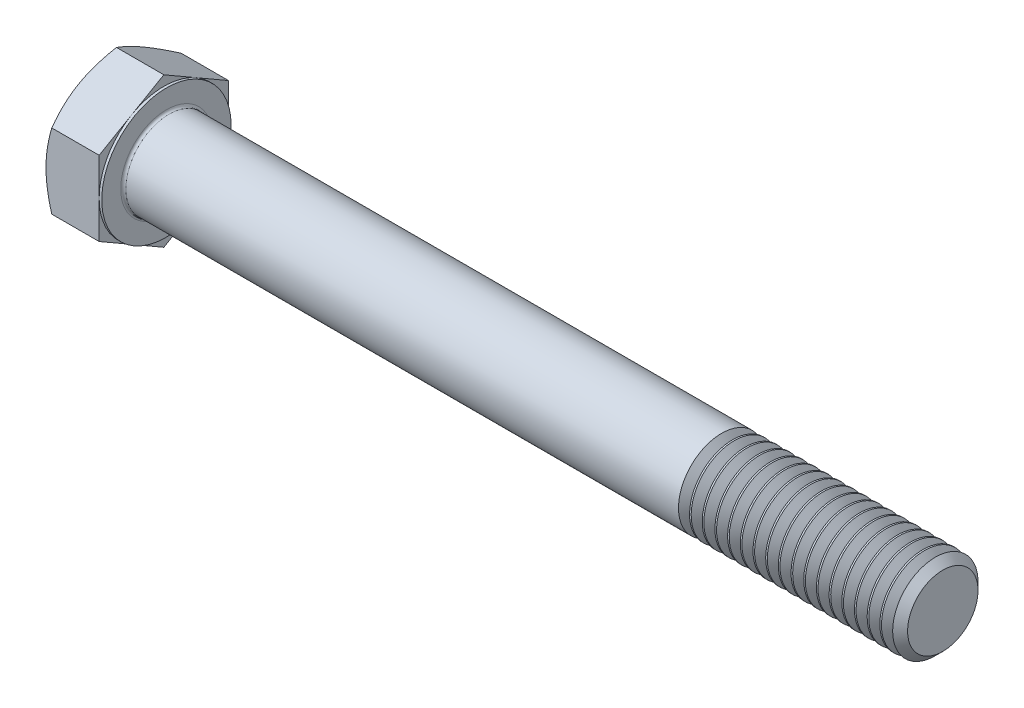
SolidWorks part; units mm, degrees
extrude "BaseHead" add sketch "Sketch1" along normal blind 8.2042
sketch "Sketch1" plane through (0, 0, 0) normal (1, 0, 0) x (0, 0, -1)
  line L0 (9.525, 5.4993) -> (9.525, -5.4993)
  line L1 (-9.525, 5.4993) -> (-9.525, -5.4993)
  line L2 (9.525, -5.4993) -> (0, -10.9985)
  line L3 (0, -10.9985) -> (-9.525, -5.4993)
  line L4 (9.525, 5.4993) -> (0, 10.9985)
  line L5 (0, 10.9985) -> (-9.525, 5.4993)
  dimension "Width_flats" = 19.05
  dimension "D2" = 120
  dimension "D3" = 9.525
  dimension "D4" = 9.525
  dimension "D5" = 9.525
revolve "HeadChamfer" cut sketch "Sketch3" angle 360 about L6
sketch "Sketch3" plane through (0, 0, 0) normal (0, 0, 1) x (1, 0, 0)
  line L0 (0, 9.525) -> (4.5169, 17.3485)
  line L1 (0, 10.9985) -> (0, 5.4993) construction
  line L2 (4.5169, 17.3485) -> (4.5169, 23.6985)
  line L3 (4.5169, 23.6985) -> (-12.7, 23.6985)
  line L4 (-12.7, 23.6985) -> (-12.7, 9.525)
  line L5 (-12.7, 9.525) -> (0, 9.525)
  line L6 (0, 0) -> (99.06, 0) construction
  line L7 (8.2042, 10.9985) -> (0, 10.9985) construction
  dimension "D1" = 9.525
  dimension "D2" = 6.35
  dimension "D3" = 12.7
  dimension "D4" = 6.35
  dimension "Head_ch_ang" = 30
material "Plain Carbon Steel"
ref_plane "Plane1" through (0, 0, 0) normal (0, 0, 1) x (1, 0, 0)
ref_plane "Plane2" through (0, 0, 0) normal (0, 1, 0) x (1, 0, 0)
ref_plane "Plane3" through (0, 0, 0) normal (1, 0, 0) x (0, 0, -1)
sketch "BodySke" plane through (0, 0, 0) normal (0, 0, 1) x (1, 0, 0)
  line L0 (0, 5.4993) -> (0, -5.4993) construction
  line L1 (0, 0) -> (122.5042, 0)
  line L2 (0, 0) -> (0, 6.35)
  line L3 (0, 6.35) -> (121.3409, 6.35)
  line L4 (122.5042, 0) -> (122.5042, 5.1867)
  line L5 (8.2042, 10.9985) -> (8.2042, 5.4993) construction
  line L6 (122.5042, 5.1867) -> (121.3409, 6.35)
  line L7 (0, 0) -> (96.52, 0) construction
  line L8 (122.5042, -5.1867) -> (121.3409, -6.35) construction
  line L9 (0, -6.35) -> (121.3409, -6.35) construction
  line L10 (10.1575, 15.24) -> (10.1575, -1.27) construction
  line L11 (90.7542, 15.24) -> (90.7542, -1.27) construction
  line L12 (8.2042, 5.4993) -> (8.2042, -5.4993) construction
  dimension "Diameter" = 12.7
revolve "BaseBody" add sketch "BodySke" angle 360 about L7
cosmetic thread "ThreadCosmetic" [suppressed]
sketch "Sketch4" plane through (0, 0, 0) normal (0, 0, 1) x (1, 0, 0)
  line L1 (8.2042, 10.9985) -> (8.2042, 5.4993) construction
  line L2 (8.2042, 9.525) -> (7.8232, 9.525)
  line L3 (8.2042, 9.525) -> (8.2042, 36.3985)
  line L4 (8.2042, 36.3985) -> (7.8232, 36.3985)
  line L5 (0, 0) -> (95.25, 0) construction
  line L6 (0, 0) -> (96.52, 0) construction
  line L7 (7.8232, 9.525) -> (7.8232, 36.3985)
  line L8 (8.2042, 10.9985) -> (0.8507, 10.9985) construction
  dimension "D1" = 9.525
  dimension "D2" = 25.4
revolve "BearingFace" cut sketch "Sketch4" angle 360 about L5
fillet "HeadFillet" radius 0.381 1 edges at (8.2042, 0, -6.35)
sketch "ThdSchSke" plane through (0, 0, 0) normal (0, 0, 1) x (1, 0, 0)
  line L0 (90.7542, -5.1867) -> (89.9396, -6.35)
  line L1 (90.7542, -5.1867) -> (91.5688, -6.35)
  line L2 (91.5688, -6.35) -> (91.5688, -7.9375)
  line L3 (-3.175, 0) -> (5.1513, 0) construction
  line L5 (91.5688, -7.9375) -> (89.9396, -7.9375)
  line L6 (89.9396, -7.9375) -> (89.9396, -6.35)
  dimension "Thread_minor" = 10.3734
  dimension "Diameter" = 12.7
  dimension "Start" = 90.7542
revolve "ThreadSchematic" cut sketch "ThdSchSke" angle 360 about L3
pattern_linear "ThdSchPat" count 17 spacing 1.8676 along (1, 0, 0) of "ThreadSchematic"
equation "\"D3@Sketch1\" = \"Width_flats@Sketch1\" / 2"
equation "\"D4@Sketch1\" = \"D3@Sketch1\""
equation "\"D5@Sketch1\" = \"D4@Sketch1\""
equation "\"Thread_minor@ThreadCosmetic\" = \"Minor_dia@BodySke\""
equation "\"D1@Sketch3\" = \"Width_flats@Sketch1\" / 2"
equation "\"D1@Sketch4\" = \"Width_flats@Sketch1\" / 2"
equation "\"Thread_length@ThreadCosmetic\" = ((sgn( (\"Length@BodySke\" - \"Advance@BodySke\" ) - \"Thread_nom@BodySke\" )-1)*( (\"Length@BodySke\" - \"Advance@BodySke\" ) - \"Thread_nom@BodySke\" ))/-2+ \"Thread_nom@BodySke\""
equation "\"Thread_minor@ThdSchSke\" = \"Minor_dia@BodySke\""
equation "\"Diameter@ThdSchSke\" = \"Diameter@BodySke\""
equation "\"Overcut@ThdSchSke\" = \"Diameter@BodySke\" * 1.25"
equation "\"Start@ThdSchSke\" = \"Head_ht@BaseHead\" + \"Length@BodySke\" - \"Thread_length@ThreadCosmetic\"  '---Non-countersunk---"
equation "\"Num_threads@ThdSchPat\" = int( \"Thread_length@ThreadCosmetic\" / \"Advance@BodySke\" + 0.999 )  + 1"
equation "\"Advance@ThdSchPat\" = \"Thread_length@ThreadCosmetic\" /  (\"Num_threads@ThdSchPat\" - 1) 'relax it"
equation "\"Num_threads@ThdSchPat\" = \"Num_threads@ThdSchPat\" - sgn( \"Num_threads@ThdSchPat\" - 1) '---chamfered tips only---"
